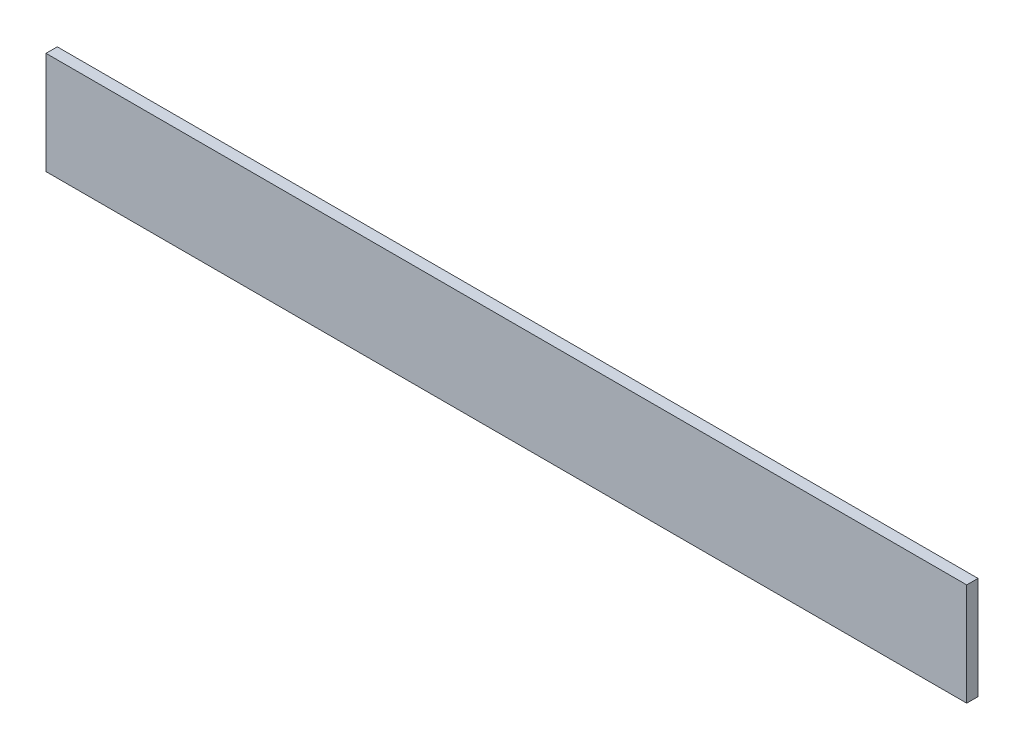
SolidWorks part; units mm, degrees
ref_plane "Front Plane" through (0, 0, 0) normal (0, 0, 1) x (1, 0, 0)
ref_plane "Top Plane" through (0, 0, 0) normal (0, 1, 0) x (1, 0, 0)
ref_plane "Right Plane" through (0, 0, 0) normal (1, 0, 0) x (0, 0, -1)
sketch "Sketch1" plane through (0, 0, 0) normal (0, 0, 1) x (1, 0, 0)
  line L0 (0, 0) -> (0, 9.23)
  line L1 (0, 9.23) -> (82.95, 9.23)
  line L2 (0, 0) -> (82.95, 0)
  line L3 (82.95, 0) -> (82.95, 9.23)
  dimension "D1" = 9.23
  dimension "D2" = 82.95
extrude "Boss-Extrude1" add sketch "Sketch1" along normal blind 1.016
